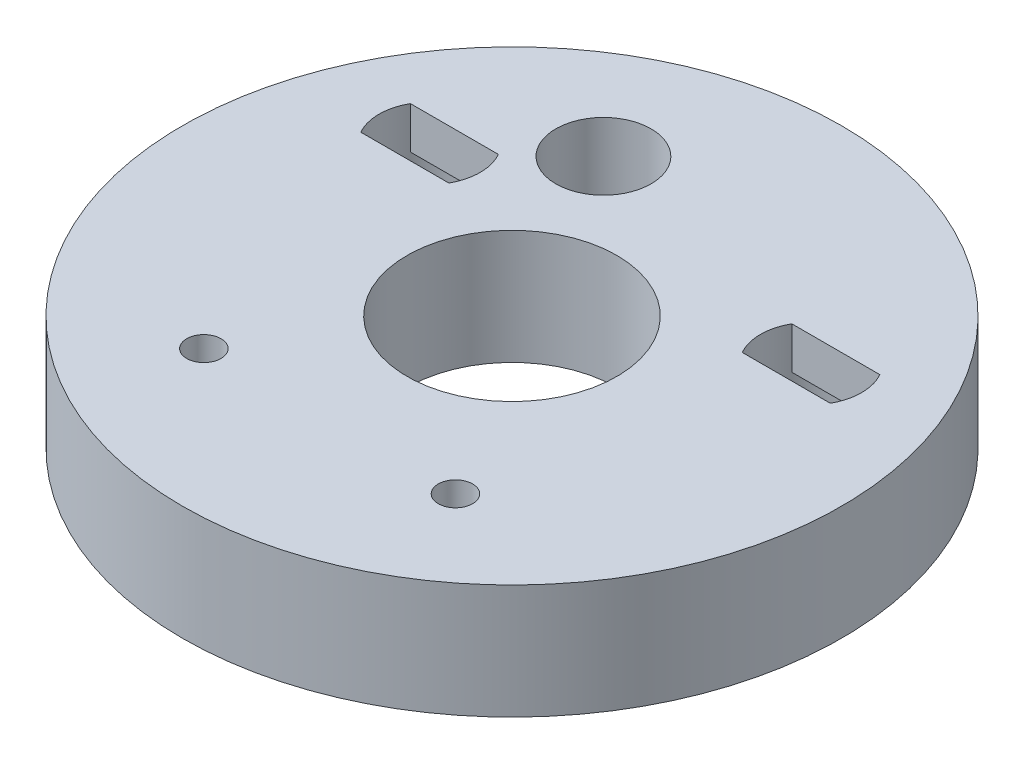
SolidWorks part; units mm, degrees
ref_plane "前视基准面" through (0, 0, 0) normal (0, 0, 1) x (1, 0, 0)
ref_plane "上视基准面" through (0, 0, 0) normal (0, 1, 0) x (1, 0, 0)
ref_plane "右视基准面" through (0, 0, 0) normal (1, 0, 0) x (0, 0, -1)
sketch "草图1" plane through (0, 0, 0) normal (0, 1, 0) x (1, 0, 0)
  line L0 (10, 5.6789) -> (-10, 5.6789) construction
  line L1 (0, 0) -> (0, 21.4139) construction
  line L2 (-6.595, -9.5611) -> (6.595, -9.5611) construction
  line L3 (-0.6445, -0.366) -> (22.2352, 12.6272) construction
  circle A0 centre (0, 0) radius 17.28
  circle A1 centre (0, 0) radius 5 construction
  circle A2 centre (0, 0) radius 5.5
  circle A3 centre (10, 5.6789) radius 2.5 construction
  circle A4 centre (-10, 5.6789) radius 2.5 construction
  circle A5 centre (6.595, -9.5611) radius 1.76 construction
  circle A6 centre (-6.595, -9.5611) radius 1.76 construction
  circle A7 centre (-10, 5.6789) radius 2.65
  circle A8 centre (-6.595, -9.5611) radius 1.9
  circle A9 centre (6.595, -9.5611) radius 1.9
  circle A10 centre (10, 5.6789) radius 2.65
  point P14 (0, 5.6789)
  point P21 (0, -9.5611)
  dimension "D1" = 34.56
  dimension "D2" = 10
  dimension "D3" = 11
  dimension "D5" = 11.5
  dimension "D7" = 5
  dimension "D8" = 13.19
  dimension "D4" = 20
  dimension "D6" = 3.52
  dimension "D10" = 5.3
  dimension "D11" = 3.8
  dimension "D9" = 15.24
extrude "凸台-拉伸1" add sketch "草图1" along normal blind 3.8
sketch "草图2" plane through (0, 3.8, 0) normal (0, 1, 0) x (1, 0, 0)
  line L0 (-7.35, 18.1851) -> (-7.35, -3.106) construction
  circle A1 centre (0, 0) radius 17.28
  circle A2 centre (0, 0) radius 17.28 construction
  circle A3 centre (-10, 5.6789) radius 2.5 construction
  circle A4 centre (-4.85, 9.6447) radius 2.5
  circle A6 centre (-10, 5.6789) radius 2.65 construction
  point P8 (0, 0)
  point P11 (-4.9083, 9.9956)
  point P12 (0, 0)
  dimension "D2" = 6.5
  dimension "D3" = 5
  dimension "D1" = 0
extrude "切除-拉伸1" cut sketch "草图2" against normal through all
sketch "草图3" plane through (0, 3.8, 0) normal (0, 1, 0) x (1, 0, 0)
  line L0 (-12.3092, 4.3789) -> (-7.6908, 4.3789)
  line L1 (-12.3092, 6.9789) -> (-7.6908, 6.9789)
  line L2 (-10, 6.9789) -> (-10, 4.3789) construction
  line L3 (0, 0) -> (0, 3.4524) construction
  line L4 (12.3092, 4.3789) -> (7.6908, 4.3789)
  line L5 (12.3092, 6.9789) -> (7.6908, 6.9789)
  circle A0 centre (6.595, -9.5611) radius 1.9 construction
  circle A1 centre (0, 0) radius 17.28
  circle A2 centre (0, 0) radius 17.28
  circle A3 centre (-6.595, -9.5611) radius 1.9 construction
  circle A5 centre (-10, 5.6789) radius 2.65 construction
  circle A6 centre (0, 0) radius 5.5 construction
  circle A7 centre (-4.85, 9.6447) radius 2.5 construction
  circle A8 centre (6.595, -9.5611) radius 1.9 construction
  circle A9 centre (-6.595, -9.5611) radius 1.9 construction
  arc A11 (-12.3092, 6.9789) -> (-12.3092, 4.3789) centre (-10, 5.6789) ccw
  circle A12 centre (0, 0) radius 5.5
  circle A13 centre (-4.85, 9.6447) radius 2.5
  arc A14 (-7.6908, 4.3789) -> (-7.6908, 6.9789) centre (-10, 5.6789) ccw
  arc A15 (7.6908, 4.3789) -> (7.6908, 6.9789) centre (10, 5.6789) cw
  arc A16 (12.3092, 6.9789) -> (12.3092, 4.3789) centre (10, 5.6789) cw
  circle A17 centre (-6.595, -9.5611) radius 0.9
  circle A18 centre (6.595, -9.5611) radius 0.9
  dimension "D3" = 1.8
  dimension "D2" = 2.6
  dimension "D1" = 0
extrude "凸台-拉伸2" add sketch "草图3" along normal blind 2.2
